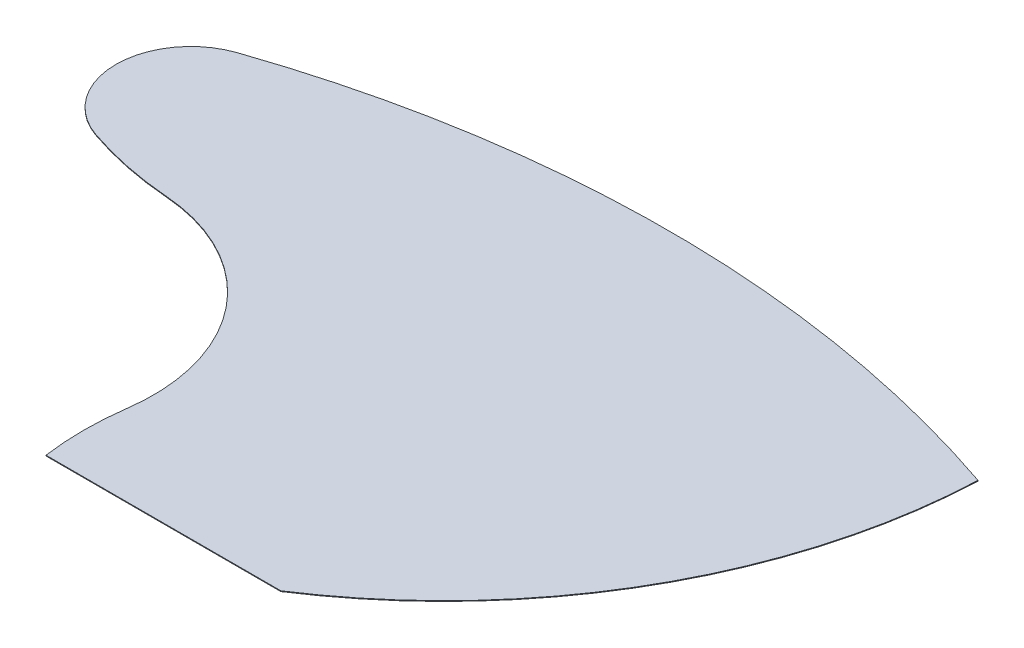
SolidWorks part; units mm, degrees
ref_plane "Front Plane" through (0, 0, 0) normal (0, 0, 1) x (1, 0, 0)
ref_plane "Top Plane" through (0, 0, 0) normal (0, 1, 0) x (1, 0, 0)
ref_plane "Right Plane" through (0, 0, 0) normal (1, 0, 0) x (0, 0, -1)
sketch "Sketch2"
sketch "Sketch1" plane through (0, 0, 0) normal (0, 1, 0) x (1, 0, 0)
  line L2 (-44.0512, 146.9643) -> (109.5118, 146.9643) construction
  line L3 (77.0118, 6.9643) -> (142.0118, 6.9643)
  line L6 (-6.9882, 171.2185) -> (-6.9882, 110.3316) construction
  line L8 (127.0118, 146.6248) -> (123.1719, 101.7889) construction
  line L9 (107.0848, 148.3314) -> (146.9389, 144.9181) construction
  line L10 (117.0483, 147.4781) -> (124.8785, 121.716) construction
  line L11 (124.8785, 121.716) -> (136.9753, 145.7715) construction
  line L12 (107.0848, 148.3314) -> (123.1719, 101.7889) construction
  line L13 (123.1719, 101.7889) -> (146.9389, 144.9181) construction
  arc A14 (7.0118, 129.9173) -> (212.0118, 129.9173) centre (109.5118, -169.7148) cw
  arc A17 (142.0118, 6.9643) -> (212.0118, 129.9173) centre (57.9998, 136.1971) ccw
  arc A22 (7.0118, 129.9173) -> (7.0118, 90.7459) centre (13.7118, 110.3316) ccw
  arc A23 (7.0118, 90.7459) -> (31.6771, 85.6694) centre (39.2819, 185.079) ccw
  arc A25 (77.0118, 29.4703) -> (31.6771, 85.6694) centre (27.8953, 36.2338) ccw
  arc A26 (77.0118, 29.4703) -> (77.0118, 6.9643) centre (158.7307, 18.2173) ccw
  point P6 (109.5118, 6.9643)
  point P19 (124.8785, 121.716)
  point P20 (117.0483, 147.4781)
  point P21 (109.5118, 146.9643)
  point P23 (136.9753, 145.7715)
  point P28 (77.0118, 29.4702)
  point P29 (0, 0)
  dimension "D1" = 20.7
  dimension "D2" = 154.14
  dimension "D3" = 219
  dimension "D6" = 49.58
  dimension "D8" = 70
  dimension "D7" = 99.7
  dimension "D15" = 82.49
  dimension "D4" = 140
  dimension "D5" = 65
  dimension "D9" = 85
  dimension "D10" = 40
  dimension "D11" = 45
  dimension "D12" = 25
  dimension "D13" = 10
  dimension "D14" = 10
extrude "Boss-Extrude1" add sketch "Sketch1" along normal blind 0.2
